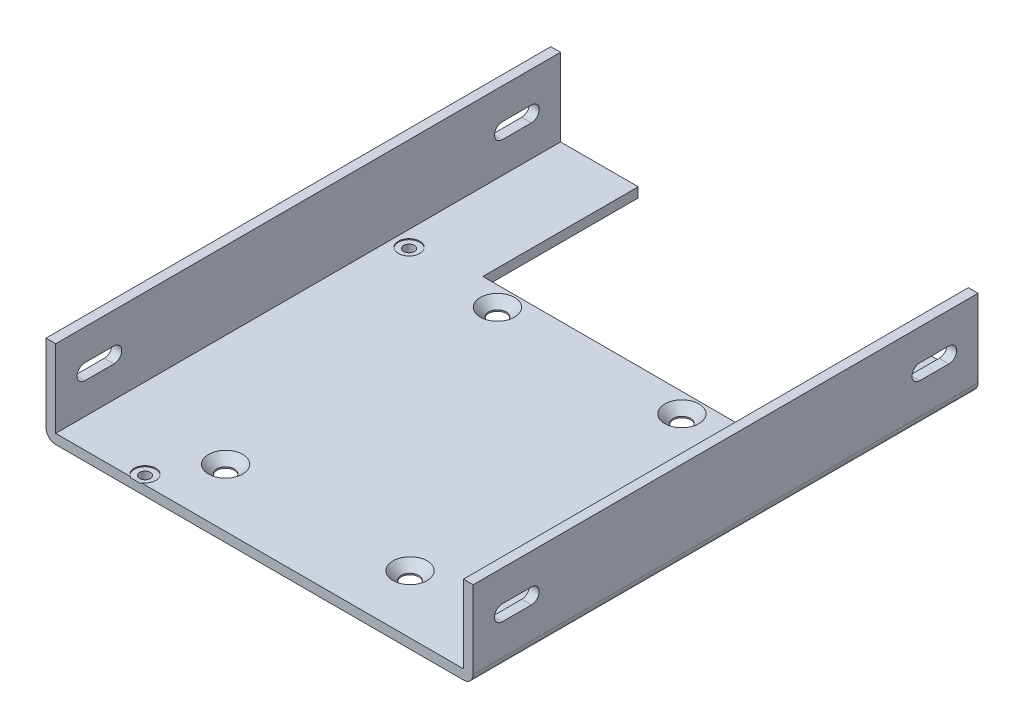
SolidWorks part; units mm, degrees
ref_plane "前视基准面" through (0, 0, 0) normal (0, 0, 1) x (1, 0, 0)
ref_plane "上视基准面" through (0, 0, 0) normal (0, 1, 0) x (1, 0, 0)
ref_plane "右视基准面" through (0, 0, 0) normal (1, 0, 0) x (0, 0, -1)
other "Configuration Table"
sketch "草图1" plane through (0, 0, 0) normal (0, 1, 0) x (1, 0, 0)
  line L11 (0, 0) -> (0, -260)
  line L12 (40, 0) -> (40, -80)
  line L14 (170, -80) -> (170, 0)
  line L20 (210, 0) -> (210, -260)
  line L21 (210, -260) -> (0, -260)
  line L22 (40, 0) -> (0, 0)
  line L23 (210, 0) -> (170, 0)
  line L24 (40, -80) -> (170, -80)
extrude "凸台-拉伸1" add sketch "草图1" along normal blind 5
hole_wizard "M8 内六角花形沉头螺钉的锥形沉头孔2" positions "草图8" profile "草图9" countersink size "M8" standard "GB" end condition through all
sketch "草图8" plane through (0, 5, 0) normal (0, 1, 0) x (1, 0, 0)
  line L13 (105, -80) -> (105, -240) construction
  line L14 (170, -80) -> (40, -80) construction
  line L16 (105, -240) -> (160, -240) construction
  line L18 (160, -240) -> (160, -80) construction
  line L19 (160, -80) -> (50, -80) construction
  line L21 (50, -80) -> (50, -240) construction
  line L22 (50, -240) -> (105, -240) construction
  line L24 (50, -160) -> (160, -160) construction
  line L25 (0, 0) -> (0, -260) construction
  line L26 (210, -260) -> (210, 0) construction
  point P64 (57.5, -90)
  point P72 (152.5, -90)
  point P73 (152.5, -230)
  point P74 (57.5, -230)
  dimension "D1" = 10
  dimension "D2" = 7.5
  dimension "D3" = 55
  dimension "D4" = 55
  dimension "D5" = 105
  dimension "D6" = 105
sketch "草图9" plane through (57.5, 5, 230) normal (1, 0, 0) x (0, 0, 1)
  line L0 (0, 0) -> (0, 5)
  line L1 (0, 5) -> (4.5, 5)
  line L2 (4.5, 5) -> (4.5, 4.3)
  line L3 (4.5, 4.3) -> (8.8, 0)
  line L5 (8.8, 0) -> (0, 0)
  line L6 (-4.5, 4.3) -> (-8.8, 0) construction
  line L11 (0, -6.35) -> (0, 107.95) construction
  dimension "通孔孔直径" = 9
  dimension "通孔孔深度" = 5
  dimension "近端锥形沉头孔直径" = 17.6
  dimension "近端锥形沉头孔角度" = 90
sketch "草图10" plane through (0, 0, 0) normal (0, 0, -1) x (-1, 0, 0)
  line L0 (0, 0) -> (0, 45)
  line L1 (0, 45) -> (5, 45)
  line L2 (5, 45) -> (5, 0)
  line L3 (5, 0) -> (0, 0)
  line L4 (-105, 0) -> (-105, 51.432) construction
  line L6 (-215, 0) -> (-210, 0)
  line L7 (-215, 45) -> (-215, 0)
  line L8 (-210, 45) -> (-215, 45)
  line L9 (-210, 0) -> (-210, 45)
extrude "凸台-拉伸2" add sketch "草图10" against normal through all
fillet "圆角1" radius 5 2 edges at (-5, 0, 130) (215, 0, 130)
sketch "草图11" plane through (215, 0, 0) normal (1, 0, 0) x (0, 0, -1)
  line L0 (0, 25) -> (-260, 25) construction
  line L3 (-260, 45) -> (0, 45) construction
  line L4 (0, 45) -> (0, 5) construction
  line L5 (-15, 29) -> (-30, 29)
  line L6 (-30, 21) -> (-15, 21)
  line L7 (-130, 45) -> (-130, 5) construction
  line L9 (-230, 21) -> (-245, 21)
  line L10 (-245, 29) -> (-230, 29)
  arc A0 (-15, 21) -> (-15, 29) centre (-15, 25) ccw
  arc A1 (-30, 29) -> (-30, 21) centre (-30, 25) ccw
  arc A2 (-230, 29) -> (-230, 21) centre (-230, 25) cw
  arc A3 (-245, 21) -> (-245, 29) centre (-245, 25) cw
  dimension "D2" = 15
  dimension "D1" = 20
  dimension "D3" = 15
extrude "切除-拉伸5" cut sketch "草图11" against normal through all
hole_wizard "M5 六角头螺栓的柱形沉头孔1" positions "草图12" profile "草图13" counterbore size "M5" standard "GB" end condition through all
sketch "草图12" plane through (0, 5, 0) normal (0, 1, 0) x (1, 0, 0)
  line L0 (105, -80) -> (105, -260) construction
  line L1 (170, -80) -> (40, -80) construction
  line L2 (0, -260) -> (210, -260) construction
  line L4 (105, -80) -> (8.1113, -80) construction
  line L6 (50, -80) -> (50, -115.9484) construction
  line L8 (2, -80) -> (2, -111.3272) construction
  line L9 (8, -86) -> (8, -190.8042) construction
  line L11 (8, -86) -> (43.0108, -86) construction
  line L14 (160, -80) -> (160, -102.8532) construction
  line L18 (170, -170) -> (196.7798, -170) construction
  line L22 (160, -80) -> (210, -80) construction
  line L23 (210, -260) -> (210, 0) construction
  line L25 (185, -80) -> (185, -106.6929) construction
  line L28 (168.25, -170) -> (168.25, -127) construction
  line L30 (168.25, -127) -> (201.75, -127) construction
  line L32 (201.75, -127) -> (201.75, -213) construction
  line L34 (201.75, -213) -> (168.25, -213) construction
  line L35 (168.25, -213) -> (168.25, -170) construction
  point P28 (8, -86)
  point P41 (41.25, -255.25)
  point P99 (176.25, -129.5)
  dimension "D2" = 6
  dimension "D1" = 55
  dimension "D3" = 6
  dimension "D4" = 169.25
  dimension "D5" = 33.25
  dimension "D6" = 8
  dimension "D7" = 2.5
sketch "草图13" plane through (176.25, 5, 129.5) normal (1, 0, 0) x (0, 0, 1)
  line L0 (0, 0) -> (0, 5)
  line L1 (0, 5) -> (2.75, 5)
  line L3 (2.75, 5) -> (2.75, 0.5)
  line L4 (2.75, 0.5) -> (5.5, 0.5)
  line L5 (5.5, 0.5) -> (5.5, 0)
  line L7 (5.5, 0) -> (0, 0)
  line L11 (0, -6.35) -> (0, 107.95) construction
  dimension "通孔孔直径" = 5.5
  dimension "通孔孔深度" = 5
  dimension "柱形沉头孔直径" = 11
  dimension "柱形沉头孔深度" = 0.5
